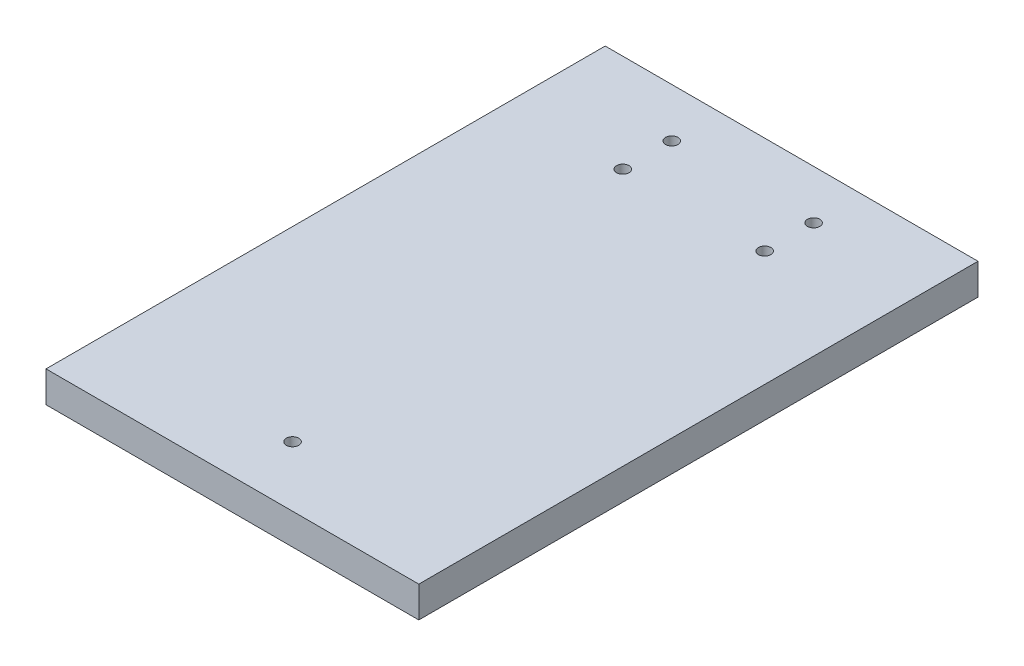
SolidWorks part; units mm, degrees
ref_plane "Front Plane" through (0, 0, 0) normal (0, 0, 1) x (1, 0, 0)
ref_plane "Top Plane" through (0, 0, 0) normal (0, 1, 0) x (1, 0, 0)
ref_plane "Right Plane" through (0, 0, 0) normal (1, 0, 0) x (0, 0, -1)
sketch "Sketch1" plane through (0, 0, 0) normal (0, 1, 0) x (1, 0, 0)
  line L0 (0, -57.15) -> (0, 57.15) construction
  line L1 (-38.1, -57.15) -> (38.1, -57.15)
  line L2 (-38.1, -57.15) -> (-38.1, 57.15)
  line L3 (-38.1, 57.15) -> (38.1, 57.15)
  line L4 (38.1, -57.15) -> (38.1, 57.15)
  line L5 (-38.1, -57.15) -> (38.1, 57.15) construction
  line L6 (-38.1, 57.15) -> (38.1, -57.15) construction
  circle A0 centre (-14.5, 47.15) radius 1.27
  circle A1 centre (14.5, 47.15) radius 1.27
  circle A2 centre (0, -44.85) radius 1.27
  circle A3 centre (-14.5, 37.15) radius 1.27
  circle A4 centre (14.5, 37.15) radius 1.27
  point P0 (0, 0)
  point P17 (0, 0)
  point P18 (0, 0)
  point P19 (0, 0)
  dimension "D1" = 2.54
  dimension "D2" = 76.2
  dimension "D3" = 114.3
  dimension "D4" = 29
  dimension "D5" = 82
  dimension "D6" = 10
  dimension "D7" = 10
extrude "Boss-Extrude1" add sketch "Sketch1" along normal blind 6.35
